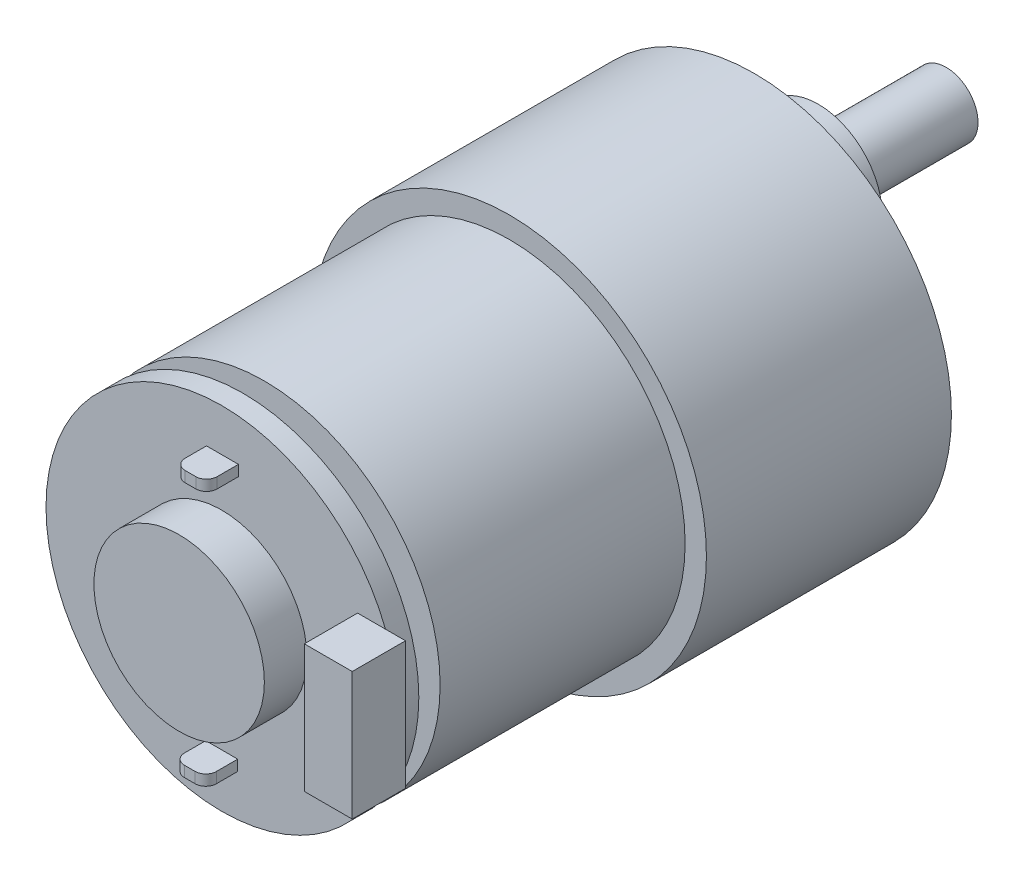
SolidWorks part; units mm, degrees
ref_plane "前视基准面" through (0, 0, 0) normal (0, 0, 1) x (1, 0, 0)
ref_plane "上视基准面" through (0, 0, 0) normal (0, 1, 0) x (1, 0, 0)
ref_plane "右视基准面" through (0, 0, 0) normal (1, 0, 0) x (0, 0, -1)
sketch "草图1" plane through (0, 0, 0) normal (0, 0, 1) x (1, 0, 0)
  circle A0 centre (0, 0) radius 18.5
extrude "凸台-拉伸3" add sketch "草图1" along normal blind 23 contours A0
sketch "草图3" plane through (0, 0, 23) normal (0, 0, 1) x (1, 0, 0)
  circle A0 centre (0, 0) radius 16.5
extrude "凸台-拉伸4" add sketch "草图3" along normal blind 23
sketch "草图4" plane through (0, 0, 0) normal (0, 0, -1) x (-1, 0, 0)
  circle A0 centre (0, 7) radius 6
  dimension "D1" = 7
extrude "凸台-拉伸5" add sketch "草图4" along normal blind 6 contours A0
sketch "草图6" plane through (0, 0, -6) normal (0, 0, -1) x (-1, 0, 0)
  circle A0 centre (0, 7) radius 3
extrude "凸台-拉伸6" add sketch "草图6" along normal blind 12
sketch "草图7" plane through (0, 0, 46) normal (0, 0, 1) x (1, 0, 0)
  circle A0 centre (0, 0) radius 2
extrude "凸台-拉伸7" add sketch "草图7" along normal blind 2
sketch "草图8" plane through (0, 0, 46) normal (0, 0, 1) x (1, 0, 0)
  line L0 (-1.5, -11.5) -> (1.5, -11.5)
  line L1 (-1.4335, 12.5) -> (1.5665, 12.5)
  line L2 (-1.4335, 12.5) -> (-1.4335, 11.5)
  line L3 (-1.4335, 11.5) -> (1.5665, 11.5)
  line L4 (1.5665, 12.5) -> (1.5665, 11.5)
  line L5 (-1.4335, 12.5) -> (1.5665, 11.5) construction
  line L6 (-1.4335, 11.5) -> (1.5665, 12.5) construction
  line L7 (-1.5, -11.5) -> (-1.5, -12.5)
  line L8 (-1.5, -12.5) -> (1.5, -12.5)
  line L9 (1.5, -11.5) -> (1.5, -12.5)
  line L10 (-1.5, -11.5) -> (1.5, -12.5) construction
  line L11 (-1.5, -12.5) -> (1.5, -11.5) construction
  point P0 (0.0665, 12)
  point P5 (0, -12)
  dimension "D1" = 3
  dimension "D2" = 1
  dimension "D3" = 12
  dimension "D4" = 12
extrude "凸台-拉伸8" add sketch "草图8" along normal blind 7
sketch "草图9" plane through (0, 0, 48) normal (0, 0, 1) x (1, 0, 0)
  circle A0 centre (0, 0) radius 16.5
extrude "凸台-拉伸9" add sketch "草图9" along normal blind 2
sketch "草图10" plane through (0, 0, 50) normal (0, 0, 1) x (1, 0, 0)
  line L1 (12.75, 6) -> (17.25, 6)
  line L2 (12.75, 6) -> (12.75, -6)
  line L3 (12.75, -6) -> (17.25, -6)
  line L4 (17.25, 6) -> (17.25, -6)
  line L5 (12.75, 6) -> (17.25, -6) construction
  line L6 (12.75, -6) -> (17.25, 6) construction
  point P0 (15, 0)
  dimension "D1" = 15
  dimension "D2" = 4.5
  dimension "D3" = 12
extrude "凸台-拉伸10" add sketch "草图10" along normal blind 5
fillet "圆角1" radius 1 4 edges at (-1.5, -12, 53) (1.5, -12, 53) (-1.4335, 12, 53) (1.5665, 12, 53)
sketch "草图11" plane through (0, 0, 50) normal (0, 0, 1) x (1, 0, 0)
  circle A0 centre (0, 0) radius 8
extrude "凸台-拉伸11" add sketch "草图11" along normal blind 4
sketch "草图12" plane through (0, 0, 0) normal (0, 0, -1) x (-1, 0, 0)
  circle A0 centre (0, 0) radius 15.5
  circle A1 centre (15.5, 0) radius 1.6
  circle A2 centre (7.75, -13.4234) radius 1.6
  circle A3 centre (-7.75, -13.4234) radius 1.6
  circle A4 centre (-15.5, 0) radius 1.6
  circle A5 centre (-7.75, 13.4234) radius 1.6
  circle A6 centre (7.75, 13.4234) radius 1.6
  point P18 (0, 0)
  dimension "D1" = 6
extrude "切除-拉伸1" cut sketch "草图12" against normal blind 2 contours A1 | A2 | A3 | A4 | A5 | A6
